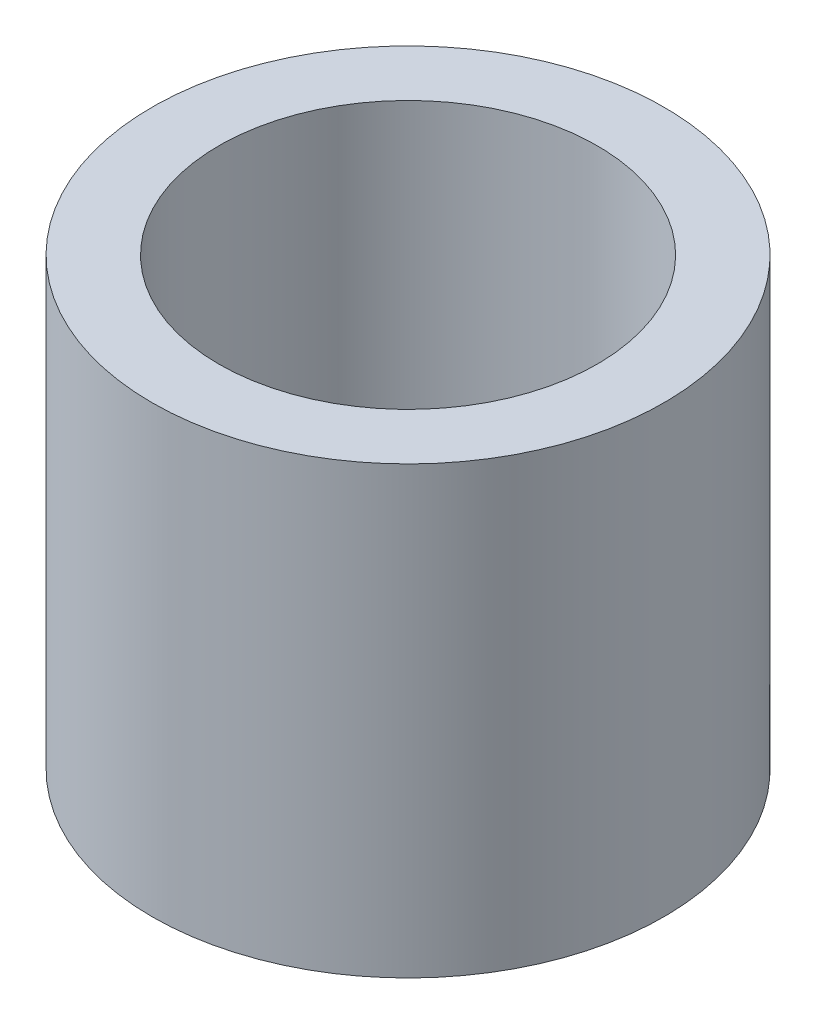
SolidWorks part; units mm, degrees
ref_plane "Спереди" through (0, 0, 0) normal (0, 0, 1) x (1, 0, 0)
ref_plane "Сверху" through (0, 0, 0) normal (0, 1, 0) x (1, 0, 0)
ref_plane "Справа" through (0, 0, 0) normal (1, 0, 0) x (0, 0, -1)
sketch "Эскиз1" plane through (0, 0, 0) normal (0, 1, 0) x (1, 0, 0)
  circle A0 centre (0, 0) radius 23
  dimension "D1" = 46
extrude "Бобышка-Вытянуть1" add sketch "Эскиз1" along normal blind 6
sketch "Эскиз2" plane through (0, 6, 0) normal (0, 1, 0) x (1, 0, 0)
  circle A0 centre (0, 0) radius 23
  circle A1 centre (0, 0) radius 17
  circle A2 centre (0, 0) radius 23 construction
  dimension "D1" = 34
  dimension "D2" = 0
extrude "Бобышка-Вытянуть2" add sketch "Эскиз2" along normal blind 34
